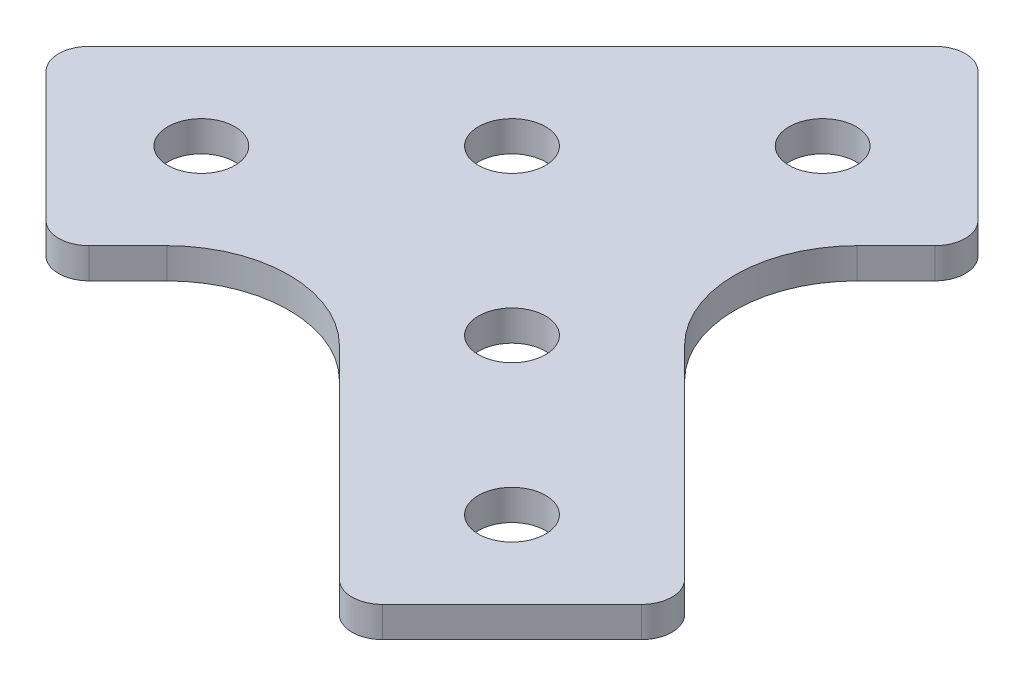
SolidWorks part; units mm, degrees
material "5052-H32"
ref_plane "Front Plane" through (0, 0, 0) normal (0, 0, 1) x (1, 0, 0)
ref_plane "Top Plane" through (0, 0, 0) normal (0, 1, 0) x (1, 0, 0)
ref_plane "Right Plane" through (0, 0, 0) normal (1, 0, 0) x (0, 0, -1)
sketch "Sketch1" plane through (0, 0, 0) normal (0, 1, 0) x (1, 0, 0)
  line L0 (-17.9605, 17.9605) -> (0, 35.921)
  line L5 (32.3289, -32.3289) -> (0, 0)
  line L6 (32.3289, -32.3289) -> (50.2894, -14.3684)
  line L7 (50.2894, -14.3684) -> (17.9605, 17.9605)
  line L9 (0, 0) -> (-31.4309, -31.4309)
  line L11 (-17.9605, 17.9605) -> (-49.3914, -13.4704)
  line L12 (-31.4309, -31.4309) -> (-49.3914, -13.4704)
  line L13 (0, 35.921) -> (17.9605, 17.9605)
  line L14 (-17.9605, 17.9605) -> (0, 0) construction
  line L15 (17.9605, 17.9605) -> (0, 0) construction
  line L16 (0, 0) -> (0, 35.921) construction
  point P3 (0, 17.9605)
  dimension "D1" = 25.4
  dimension "D2" = 25.4
  dimension "D5" = 90
  dimension "D4" = 45.72
  dimension "D3" = 57.15
extrude "Boss-Extrude1" add sketch "Sketch1" along normal blind 3.175 contours L0 L13 L7 L6 L5 L9 L12 L11
sketch "Sketch2" plane through (0, 3.175, 0) normal (0, 1, 0) x (1, 0, 0)
  line L0 (-49.3914, -13.4704) -> (-31.4309, -31.4309) construction
  line L1 (-32.3289, -14.3684) -> (-40.4112, -22.4506) construction
  line L2 (50.2894, -14.3684) -> (32.3289, -32.3289) construction
  line L3 (33.2269, -15.2664) -> (41.3092, -23.3487) construction
  circle A0 centre (-32.3289, -14.3684) radius 3.4925
  circle A1 centre (33.2269, -15.2664) radius 3.4925
  dimension "D1" = 6.985
  dimension "D2" = 11.43
sketch "Sketch7" plane through (0, 3.175, 0) normal (0, 1, 0) x (1, 0, 0)
  line L0 (-49.3914, -13.4704) -> (-31.4309, -31.4309) construction
  line L1 (-32.3289, -14.3684) -> (-40.4112, -22.4506) construction
  line L2 (50.2894, -14.3684) -> (32.3289, -32.3289) construction
  line L3 (33.2269, -15.2664) -> (41.3092, -23.3487) construction
  circle A0 centre (-32.3289, -14.3684) radius 3.4925
  circle A1 centre (33.2269, -15.2664) radius 3.4925
  dimension "D1" = 6.985
  dimension "D2" = 11.43
extrude "Cut-Extrude2" cut sketch "Sketch2" against normal blind 3.175 contours A0
pattern_linear "LPattern5" count 3 spacing 22.86 along (0.7071, 0, -0.7071) of "Cut-Extrude2"
extrude "Cut-Extrude3" cut sketch "Sketch7" against normal blind 3.175 contours A1
pattern_linear "LPattern6" count 2 spacing 22.86 along (-0.7071, 0, -0.7071) of "Cut-Extrude3"
ref_plane "Plane1" through (8.9803, 0, -8.9803) normal (-0.7071, 0, 0.7071) x (0.7071, 0, 0.7071)
mirror "Mirror2" about plane through (8.9803, 0, -8.9803) normal (-0.7071, 0, 0.7071) of bodies 107
sketch "Sketch8" plane through (0, 3.175, 0) normal (0, 1, 0) x (1, 0, 0)
  line L0 (49.3914, 49.3914) -> (31.4309, 67.3519) construction
  line L1 (-31.4309, -31.4309) -> (-49.3914, -13.4704) construction
  line L2 (49.3914, 49.3914) -> (31.4309, 67.3519)
  line L3 (-31.4309, -31.4309) -> (-49.3914, -13.4704)
  line L4 (-49.3914, -13.4704) -> (-31.4309, -31.4309)
  line L5 (-49.3914, -13.4704) -> (-33.2269, 2.6941)
  line L6 (-31.4309, -31.4309) -> (-15.2664, -15.2664)
  line L7 (-33.2269, 2.6941) -> (-15.2664, -15.2664)
  line L8 (31.4309, 67.3519) -> (49.3914, 49.3914)
  line L9 (31.4309, 67.3519) -> (15.2664, 51.1875)
  line L10 (49.3914, 49.3914) -> (33.2269, 33.2269)
  line L11 (15.2664, 51.1875) -> (33.2269, 33.2269)
  circle M7 centre (-32.3289, -14.3684) radius 3.4925
  line M8 (-31.4309, -31.4309) -> (0, 0)
  line M14 (17.9605, 17.9605) -> (49.3914, 49.3914)
  line M15 (49.3914, 49.3914) -> (31.4309, 67.3519)
  line M16 (31.4309, 67.3519) -> (-49.3914, -13.4704)
  line M17 (-49.3914, -13.4704) -> (-31.4309, -31.4309)
  circle M22 centre (32.3289, 50.2894) radius 3.4925
  dimension "D1" = 22.86
extrude "Cut-Extrude4" cut sketch "Sketch8" against normal through all contours L7 M16 M17 M8 M7 | L11 M16 M14 M15 M22
fillet "Fillet3" radius 12.7 2 edges at (17.9605, 1.5875, -17.9605) (0, 1.5875, 0)
fillet "Fillet4" radius 3.175 6 edges at (15.2664, 1.5875, -51.1875) (33.2269, 1.5875, -33.2269) (50.2894, 1.5875, 14.3684) (32.3289, 1.5875, 32.3289) (-33.2269, 1.5875, -2.6941) (-15.2664, 1.5875, 15.2664)
equation "\"InnerAngle\"= 90"
equation "\"StockThickness\"= .125in"
equation "\"HoleDiameter\"= .275in"
equation "\"BarWidth\"= 1in"
equation "\"HoleSpacing\"=0.9"
equation "\"AdditionalHoleCount\"= 2"
equation "\"D1@Sketch1\"=\"BarWidth\""
equation "\"D2@Sketch1\"= \"BarWidth\""
equation "\"WingLength\"= ( \"AdditionalHoleCount\" ) * \"HoleSpacing\""
equation "\"D5@Sketch1\"=\"InnerAngle\""
equation "\"D1@Boss-Extrude1\"=\"StockThickness\""
equation "\"D1@Sketch2\"=\"HoleDiameter\""
equation "\"D2@Sketch2\"=\"HoleSpacing\"/2"
equation "\"D3@LPattern5\"=\"HoleSpacing\""
equation "\"D1@LPattern5\"=\"AdditionalHoleCount\"+1"
equation "\"D2@Sketch7\"=\"HoleSpacing\"/2"
equation "\"D1@Sketch7\"=\"HoleDiameter\""
equation "\"D3@LPattern6\"=\"HoleSpacing\""
equation "\"D1@LPattern6\"=\"AdditionalHoleCount\""
equation "\"D4@Sketch1\"=\"WingLength\""
equation "\"D3@Sketch1\"=\"WingLength\"+\"HoleSpacing\"/2"
